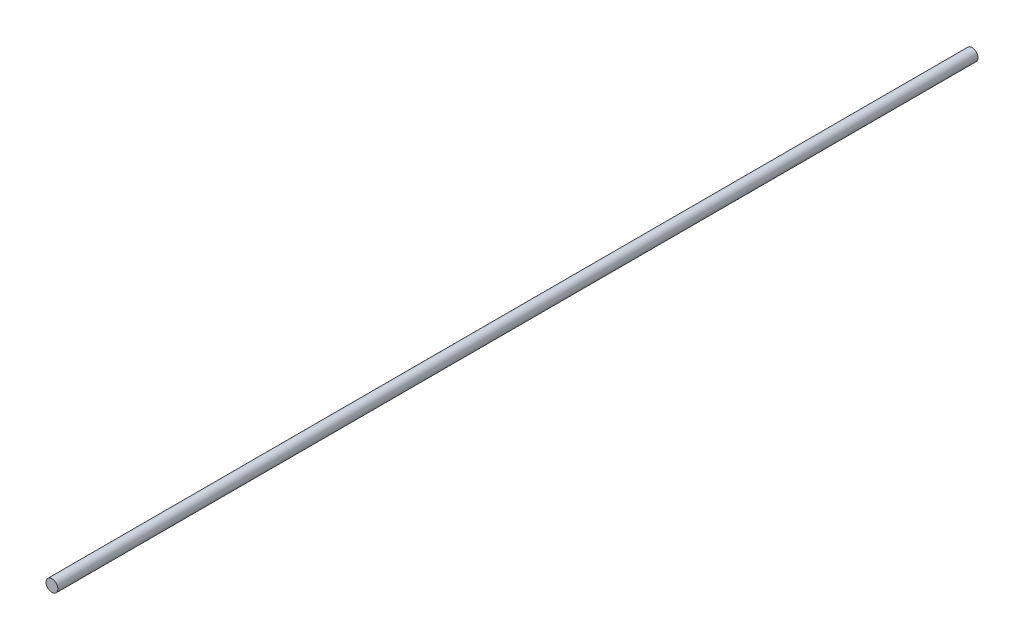
SolidWorks part; units mm, degrees
ref_plane "Front Plane" through (0, 0, 0) normal (0, 0, 1) x (1, 0, 0)
ref_plane "Top Plane" through (0, 0, 0) normal (0, 1, 0) x (1, 0, 0)
ref_plane "Right Plane" through (0, 0, 0) normal (1, 0, 0) x (0, 0, -1)
sketch "Sketch1" plane through (0, 0, 0) normal (0, 0, 1) x (1, 0, 0)
  circle A0 centre (0, 0) radius 4
  dimension "D1" = 8
extrude "Boss-Extrude1" add sketch "Sketch1" along normal blind 620
